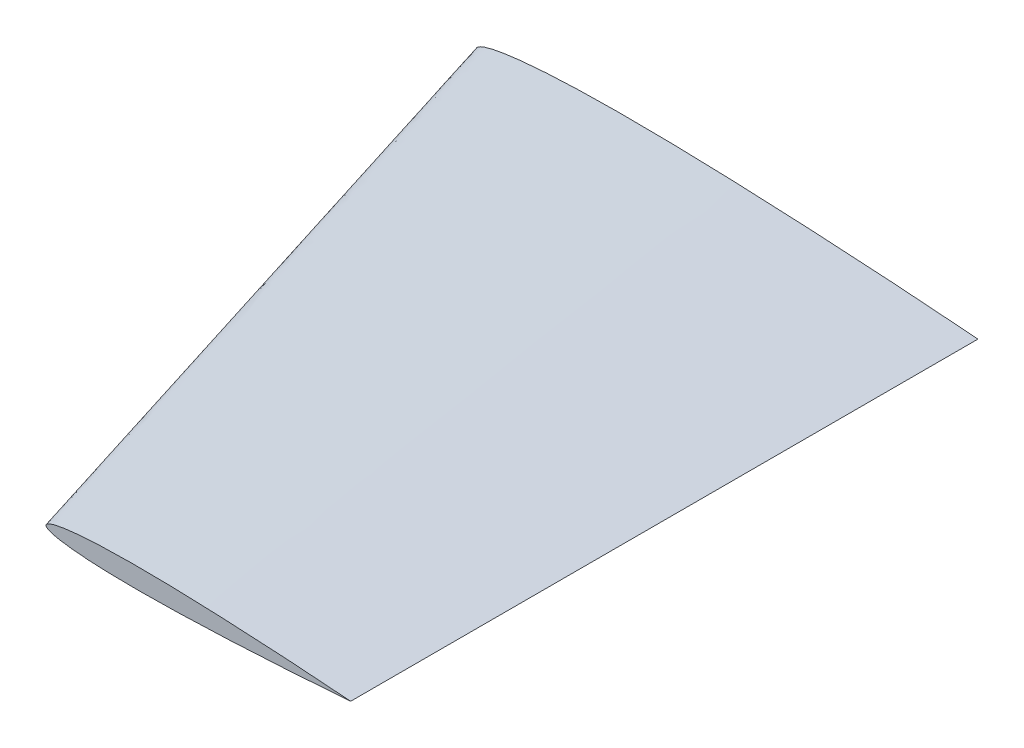
SolidWorks part; units mm, degrees
ref_plane "Спереди" through (0, 0, 0) normal (0, 0, 1) x (1, 0, 0)
ref_plane "Сверху" through (0, 0, 0) normal (0, 1, 0) x (1, 0, 0)
ref_plane "Справа" through (0, 0, 0) normal (1, 0, 0) x (0, 0, -1)
curve "нерв11"
  spline degree 3 poles (280, 0, 0) (279.9079, 0.0075, 0) (279.5399, 0.0373, 0) (278.7133, 0.1038, 0) (277.3394, 0.2136, 0) (275.4234, 0.3662, 0) (272.9728, 0.5586, 0) (269.9976, 0.79, 0) (266.5093, 1.0574, 0) (262.5218, 1.3575, 0) (258.0506, 1.6881, 0) (253.1137, 2.0453, 0) (247.7303, 2.4266, 0) (241.9218, 2.8274, 0) (235.7109, 3.2451, 0) (229.1225, 3.6764, 0) (222.1821, 4.1166, 0) (214.9176, 4.5633, 0) (207.3573, 5.0121, 0) (199.5312, 5.4596, 0) (191.4701, 5.9019, 0) (183.206, 6.336, 0) (174.7713, 6.7567, 0) (166.1995, 7.1603, 0) (157.5242, 7.5437, 0) (148.7797, 7.901, 0) (140.0006, 8.229, 0) (131.2215, 8.5229, 0) (122.4769, 8.7782, 0) (113.8015, 8.9914, 0) (105.2296, 9.1574, 0) (96.7949, 9.273, 0) (88.5305, 9.3348, 0) (80.4692, 9.3396, 0) (72.6428, 9.2852, 0) (65.0822, 9.1701, 0) (57.8173, 8.9931, 0) (50.8764, 8.7536, 0) (44.2874, 8.4522, 0) (38.0758, 8.0908, 0) (32.2665, 7.6702, 0) (26.8819, 7.1938, 0) (21.9435, 6.6644, 0) (17.4704, 6.0858, 0) (13.4799, 5.4625, 0) (9.9879, 4.7977, 0) (7.0046, 4.0976, 0) (4.5467, 3.3651, 0) (2.5986, 2.6073, 0) (1.2079, 1.8188, 0) (0.2201, 0.9919, 0) (0.0666, 0.3003, 0) (0, 0, 0) knots 0 0 0 0 0.000983 0.003927 0.00882 0.015644 0.024371 0.034965 0.047385 0.061583 0.077499 0.095072 0.114231 0.134902 0.157001 0.180442 0.20513 0.23097 0.257857 0.285686 0.314347 0.343727 0.373708 0.404173 0.435002 0.466072 0.497261 0.528445 0.559503 0.590311 0.620748 0.650695 0.680035 0.708653 0.736438 0.76328 0.789079 0.813733 0.837149 0.859235 0.879912 0.899099 0.916729 0.932736 0.947069 0.959681 0.970541 0.979636 0.986978 0.992635 0.996802 1 1 1 1
curve "нерв12"
  spline degree 3 poles (0, 0, 0) (0.0666, -0.3003, 0) (0.2201, -0.9919, 0) (1.2079, -1.8188, 0) (2.5986, -2.6073, 0) (4.5467, -3.3651, 0) (7.0046, -4.0976, 0) (9.9879, -4.7977, 0) (13.4799, -5.4625, 0) (17.4704, -6.0858, 0) (21.9435, -6.6644, 0) (26.8819, -7.1938, 0) (32.2665, -7.6702, 0) (38.0758, -8.0908, 0) (44.2874, -8.4522, 0) (50.8764, -8.7536, 0) (57.8173, -8.9931, 0) (65.0822, -9.1701, 0) (72.6428, -9.2852, 0) (80.4692, -9.3396, 0) (88.5305, -9.3348, 0) (96.7949, -9.273, 0) (105.2296, -9.1574, 0) (113.8015, -8.9914, 0) (122.4769, -8.7782, 0) (131.2215, -8.5229, 0) (140.0006, -8.229, 0) (148.7797, -7.901, 0) (157.5242, -7.5437, 0) (166.1995, -7.1603, 0) (174.7713, -6.7567, 0) (183.206, -6.336, 0) (191.4701, -5.9019, 0) (199.5312, -5.4596, 0) (207.3573, -5.0121, 0) (214.9176, -4.5633, 0) (222.1821, -4.1166, 0) (229.1225, -3.6764, 0) (235.7109, -3.2451, 0) (241.9218, -2.8274, 0) (247.7303, -2.4266, 0) (253.1137, -2.0453, 0) (258.0506, -1.6881, 0) (262.5218, -1.3575, 0) (266.5093, -1.0574, 0) (269.9976, -0.79, 0) (272.9728, -0.5586, 0) (275.4234, -0.3662, 0) (277.3394, -0.2136, 0) (278.7133, -0.1038, 0) (279.5399, -0.0373, 0) (279.9079, -0.0075, 0) (280, 0, 0) knots 0 0 0 0 0.003198 0.007365 0.013022 0.020364 0.029459 0.040319 0.052931 0.067264 0.083271 0.100901 0.120088 0.140765 0.162851 0.186267 0.210921 0.23672 0.263562 0.291347 0.319965 0.349305 0.379252 0.409689 0.440497 0.471555 0.502739 0.533928 0.564998 0.595827 0.626292 0.656273 0.685653 0.714314 0.742143 0.76903 0.79487 0.819558 0.842999 0.865098 0.885769 0.904928 0.922501 0.938417 0.952615 0.965035 0.975629 0.984356 0.99118 0.996073 0.999017 1 1 1 1
curve "Кривая5"
  spline degree 3 poles (55, 0, 0) (55.0536, -0.2413, 0) (55.1769, -0.7971, 0) (55.9706, -1.4615, 0) (57.0882, -2.0952, 0) (58.6536, -2.7041, 0) (60.6287, -3.2927, 0) (63.026, -3.8553, 0) (65.8321, -4.3895, 0) (69.0387, -4.8904, 0) (72.6332, -5.3553, 0) (76.6015, -5.7807, 0) (80.9284, -6.1635, 0) (85.5966, -6.5015, 0) (90.5881, -6.792, 0) (95.8828, -7.0342, 0) (101.4603, -7.2266, 0) (107.2982, -7.3688, 0) (113.3737, -7.4613, 0) (119.6627, -7.505, 0) (126.1406, -7.5012, 0) (132.7816, -7.4515, 0) (139.5595, -7.3586, 0) (146.4477, -7.2252, 0) (153.419, -7.0539, 0) (160.4458, -6.8488, 0) (167.5005, -6.6126, 0) (174.5551, -6.349, 0) (181.582, -6.0619, 0) (188.5532, -5.7538, 0) (195.4413, -5.4295, 0) (202.2191, -5.0914, 0) (208.8599, -4.7426, 0) (215.3376, -4.3872, 0) (221.6264, -4.0276, 0) (227.7016, -3.667, 0) (233.5392, -3.308, 0) (239.1163, -2.9543, 0) (244.4106, -2.6077, 0) (249.4014, -2.272, 0) (254.069, -1.95, 0) (258.3949, -1.6435, 0) (262.3621, -1.3565, 0) (265.955, -1.0909, 0) (269.1593, -0.8497, 0) (271.9624, -0.6348, 0) (274.3532, -0.4489, 0) (276.3224, -0.2943, 0) (277.862, -0.1716, 0) (278.9661, -0.0834, 0) (279.6303, -0.03, 0) (279.926, -0.006, 0) (280, 0, 0) knots 0 0 0 0 0.003198 0.007365 0.013022 0.020364 0.029459 0.040319 0.052931 0.067264 0.083271 0.100901 0.120088 0.140765 0.162851 0.186267 0.210921 0.23672 0.263562 0.291347 0.319965 0.349305 0.379252 0.409689 0.440497 0.471555 0.502739 0.533928 0.564998 0.595827 0.626292 0.656273 0.685653 0.714314 0.742143 0.76903 0.79487 0.819558 0.842999 0.865098 0.885769 0.904928 0.922501 0.938417 0.952615 0.965035 0.975629 0.984356 0.99118 0.996073 0.999017 1 1 1 1
curve "Кривая6"
  spline degree 3 poles (280, 0, 0) (279.926, 0.006, 0) (279.6303, 0.03, 0) (278.9661, 0.0834, 0) (277.862, 0.1716, 0) (276.3224, 0.2943, 0) (274.3532, 0.4489, 0) (271.9624, 0.6348, 0) (269.1593, 0.8497, 0) (265.955, 1.0909, 0) (262.3621, 1.3565, 0) (258.3949, 1.6435, 0) (254.069, 1.95, 0) (249.4014, 2.272, 0) (244.4106, 2.6077, 0) (239.1163, 2.9543, 0) (233.5392, 3.308, 0) (227.7016, 3.667, 0) (221.6264, 4.0276, 0) (215.3376, 4.3872, 0) (208.8599, 4.7426, 0) (202.2191, 5.0914, 0) (195.4413, 5.4295, 0) (188.5532, 5.7538, 0) (181.582, 6.0619, 0) (174.5551, 6.349, 0) (167.5005, 6.6126, 0) (160.4458, 6.8488, 0) (153.419, 7.0539, 0) (146.4477, 7.2252, 0) (139.5595, 7.3586, 0) (132.7816, 7.4515, 0) (126.1406, 7.5012, 0) (119.6627, 7.505, 0) (113.3737, 7.4613, 0) (107.2982, 7.3688, 0) (101.4603, 7.2266, 0) (95.8828, 7.0342, 0) (90.5881, 6.792, 0) (85.5966, 6.5015, 0) (80.9284, 6.1635, 0) (76.6015, 5.7807, 0) (72.6332, 5.3553, 0) (69.0387, 4.8904, 0) (65.8321, 4.3895, 0) (63.026, 3.8553, 0) (60.6287, 3.2927, 0) (58.6536, 2.7041, 0) (57.0882, 2.0952, 0) (55.9706, 1.4615, 0) (55.1769, 0.7971, 0) (55.0536, 0.2413, 0) (55, 0, 0) knots 0 0 0 0 0.000983 0.003927 0.00882 0.015644 0.024371 0.034965 0.047385 0.061583 0.077499 0.095072 0.114231 0.134902 0.157001 0.180442 0.20513 0.23097 0.257857 0.285686 0.314347 0.343727 0.373708 0.404173 0.435002 0.466072 0.497261 0.528445 0.559503 0.590311 0.620748 0.650695 0.680035 0.708653 0.736438 0.76328 0.789079 0.813733 0.837149 0.859235 0.879912 0.899099 0.916729 0.932736 0.947069 0.959681 0.970541 0.979636 0.986978 0.992635 0.996802 1 1 1 1
ref_plane "2 енрв" through (0, 0, 175) normal (0, 0, 1) x (1, 0, 0)
ref_plane "3 нерв" through (0, 0, 350) normal (0, 0, 1) x (1, 0, 0)
sketch "нерв 2" plane through (0, 0, 175) normal (0, 0, 1) x (1, 0, 0)
  spline S0 degree 3 poles (-1705.7299, -947.936) (109.1984, 46.2421) (49.2151, 4.1935) (55.9706, -1.4615) (57.0882, -2.0952) (58.6536, -2.7041) (60.6287, -3.2927) (63.026, -3.8553) (65.8321, -4.3895) (69.0387, -4.8904) (72.6332, -5.3553) (76.6015, -5.7807) (80.9284, -6.1635) (85.5966, -6.5015) (90.5881, -6.792) (95.8828, -7.0342) (101.4603, -7.2266) (107.2982, -7.3688) (113.3737, -7.4613) (119.6627, -7.505) (126.1406, -7.5012) (132.7816, -7.4515) (139.5595, -7.3586) (146.4477, -7.2252) (153.419, -7.0539) (160.4458, -6.8488) (167.5005, -6.6126) (174.5551, -6.349) (181.582, -6.0619) (188.5532, -5.7538) (195.4413, -5.4295) (202.2191, -5.0914) (208.8599, -4.7426) (215.3376, -4.3872) (221.6264, -4.0276) (227.7016, -3.667) (233.5392, -3.308) (239.1163, -2.9543) (244.4106, -2.6077) (249.4014, -2.272) (254.069, -1.95) (258.3949, -1.6435) (262.3621, -1.3565) (265.955, -1.0909) (269.1593, -0.8497) (271.9624, -0.6348) (274.3532, -0.4489) (276.3224, -0.2943) (277.862, -0.1716) (278.9661, -0.0834) (318.8848, 3.1257) (358.1271, 10.1124) (558.6291, -1979.213) knots -0.097805 -0.097805 -0.097805 -0.097805 0.003198 0.007365 0.013022 0.020364 0.029459 0.040319 0.052931 0.067264 0.083271 0.100901 0.120088 0.140765 0.162851 0.186267 0.210921 0.23672 0.263562 0.291347 0.319965 0.349305 0.379252 0.409689 0.440497 0.471555 0.502739 0.533928 0.564998 0.595827 0.626292 0.656273 0.685653 0.714314 0.742143 0.76903 0.79487 0.819558 0.842999 0.865098 0.885769 0.904928 0.922501 0.938417 0.952615 0.965035 0.975629 0.984356 0.99118 0.996073 0.999017 1.521268 1.521268 1.521268 1.521268 only from (55, 0) to (280, 0) construction
  spline S1 degree 3 poles (558.6328, 1979.2493) (358.1276, -10.1125) (318.8851, -3.1257) (278.9661, 0.0834) (277.862, 0.1716) (276.3224, 0.2943) (274.3532, 0.4489) (271.9624, 0.6348) (269.1593, 0.8497) (265.955, 1.0909) (262.3621, 1.3565) (258.3949, 1.6435) (254.069, 1.95) (249.4014, 2.272) (244.4106, 2.6077) (239.1163, 2.9543) (233.5392, 3.308) (227.7016, 3.667) (221.6264, 4.0276) (215.3376, 4.3872) (208.8599, 4.7426) (202.2191, 5.0914) (195.4413, 5.4295) (188.5532, 5.7538) (181.582, 6.0619) (174.5551, 6.349) (167.5005, 6.6126) (160.4458, 6.8488) (153.419, 7.0539) (146.4477, 7.2252) (139.5595, 7.3586) (132.7816, 7.4515) (126.1406, 7.5012) (119.6627, 7.505) (113.3737, 7.4613) (107.2982, 7.3688) (101.4603, 7.2266) (95.8828, 7.0342) (90.5881, 6.792) (85.5966, 6.5015) (80.9284, 6.1635) (76.6015, 5.7807) (72.6332, 5.3553) (69.0387, 4.8904) (65.8321, 4.3895) (63.026, 3.8553) (60.6287, 3.2927) (58.6536, 2.7041) (57.0882, 2.0952) (55.9706, 1.4615) (49.2153, -4.1933) (109.194, -46.239) (-1705.5233, 947.8229) knots -0.521271 -0.521271 -0.521271 -0.521271 0.000983 0.003927 0.00882 0.015644 0.024371 0.034965 0.047385 0.061583 0.077499 0.095072 0.114231 0.134902 0.157001 0.180442 0.20513 0.23097 0.257857 0.285686 0.314347 0.343727 0.373708 0.404173 0.435002 0.466072 0.497261 0.528445 0.559503 0.590311 0.620748 0.650695 0.680035 0.708653 0.736438 0.76328 0.789079 0.813733 0.837149 0.859235 0.879912 0.899099 0.916729 0.932736 0.947069 0.959681 0.970541 0.979636 0.986978 0.992635 0.996802 1.097801 1.097801 1.097801 1.097801 only from (280, 0) to (55, 0) construction
  spline S2 degree 3 poles (55, 0) (55.0536, -0.2413) (55.1769, -0.7971) (55.9706, -1.4615) (57.0882, -2.0952) (58.6536, -2.7041) (60.6287, -3.2927) (63.026, -3.8553) (65.8321, -4.3895) (69.0387, -4.8904) (72.6332, -5.3553) (76.6015, -5.7807) (80.9284, -6.1635) (85.5966, -6.5015) (90.5881, -6.792) (95.8828, -7.0342) (101.4603, -7.2266) (107.2982, -7.3688) (113.3737, -7.4613) (119.6627, -7.505) (126.1406, -7.5012) (132.7816, -7.4515) (139.5595, -7.3586) (146.4477, -7.2252) (153.419, -7.0539) (160.4458, -6.8488) (167.5005, -6.6126) (174.5551, -6.349) (181.582, -6.0619) (188.5532, -5.7538) (195.4413, -5.4295) (202.2191, -5.0914) (208.8599, -4.7426) (215.3376, -4.3872) (221.6264, -4.0276) (227.7016, -3.667) (233.5392, -3.308) (239.1163, -2.9543) (244.4106, -2.6077) (249.4014, -2.272) (254.069, -1.95) (258.3949, -1.6435) (262.3621, -1.3565) (265.955, -1.0909) (269.1593, -0.8497) (271.9624, -0.6348) (274.3532, -0.4489) (276.3224, -0.2943) (277.862, -0.1716) (278.9661, -0.0834) (279.6303, -0.03) (279.926, -0.006) (280, 0) knots 0 0 0 0 0.003198 0.007365 0.013022 0.020364 0.029459 0.040319 0.052931 0.067264 0.083271 0.100901 0.120088 0.140765 0.162851 0.186267 0.210921 0.23672 0.263562 0.291347 0.319965 0.349305 0.379252 0.409689 0.440497 0.471555 0.502739 0.533928 0.564998 0.595827 0.626292 0.656273 0.685653 0.714314 0.742143 0.76903 0.79487 0.819558 0.842999 0.865098 0.885769 0.904928 0.922501 0.938417 0.952615 0.965035 0.975629 0.984356 0.99118 0.996073 0.999017 1 1 1 1
  spline S3 degree 3 poles (280, 0) (279.926, 0.006) (279.6303, 0.03) (278.9661, 0.0834) (277.862, 0.1716) (276.3224, 0.2943) (274.3532, 0.4489) (271.9624, 0.6348) (269.1593, 0.8497) (265.955, 1.0909) (262.3621, 1.3565) (258.3949, 1.6435) (254.069, 1.95) (249.4014, 2.272) (244.4106, 2.6077) (239.1163, 2.9543) (233.5392, 3.308) (227.7016, 3.667) (221.6264, 4.0276) (215.3376, 4.3872) (208.8599, 4.7426) (202.2191, 5.0914) (195.4413, 5.4295) (188.5532, 5.7538) (181.582, 6.0619) (174.5551, 6.349) (167.5005, 6.6126) (160.4458, 6.8488) (153.419, 7.0539) (146.4477, 7.2252) (139.5595, 7.3586) (132.7816, 7.4515) (126.1406, 7.5012) (119.6627, 7.505) (113.3737, 7.4613) (107.2982, 7.3688) (101.4603, 7.2266) (95.8828, 7.0342) (90.5881, 6.792) (85.5966, 6.5015) (80.9284, 6.1635) (76.6015, 5.7807) (72.6332, 5.3553) (69.0387, 4.8904) (65.8321, 4.3895) (63.026, 3.8553) (60.6287, 3.2927) (58.6536, 2.7041) (57.0882, 2.0952) (55.9706, 1.4615) (55.1769, 0.7971) (55.0536, 0.2413) (55, 0) knots 0 0 0 0 0.000983 0.003927 0.00882 0.015644 0.024371 0.034965 0.047385 0.061583 0.077499 0.095072 0.114231 0.134902 0.157001 0.180442 0.20513 0.23097 0.257857 0.285686 0.314347 0.343727 0.373708 0.404173 0.435002 0.466072 0.497261 0.528445 0.559503 0.590311 0.620748 0.650695 0.680035 0.708653 0.736438 0.76328 0.789079 0.813733 0.837149 0.859235 0.879912 0.899099 0.916729 0.932736 0.947069 0.959681 0.970541 0.979636 0.986978 0.992635 0.996802 1 1 1 1
curve "Кривая7"
  spline degree 3 poles (110, 0, 0) (110.0405, -0.1823, 0) (110.1336, -0.6022, 0) (110.7334, -1.1043, 0) (111.5777, -1.583, 0) (112.7605, -2.0431, 0) (114.2528, -2.4878, 0) (116.0641, -2.9129, 0) (118.1842, -3.3165, 0) (120.607, -3.695, 0) (123.3229, -4.0462, 0) (126.3212, -4.3677, 0) (129.5904, -4.6569, 0) (133.1175, -4.9122, 0) (136.8888, -5.1317, 0) (140.8893, -5.3147, 0) (145.1033, -5.4601, 0) (149.5142, -5.5675, 0) (154.1046, -5.6375, 0) (158.8563, -5.6704, 0) (163.7507, -5.6675, 0) (168.7683, -5.63, 0) (173.8894, -5.5598, 0) (179.0938, -5.459, 0) (184.361, -5.3296, 0) (189.6702, -5.1746, 0) (195.0004, -4.9962, 0) (200.3305, -4.797, 0) (205.6397, -4.5801, 0) (210.9069, -4.3473, 0) (216.1112, -4.1023, 0) (221.2322, -3.8468, 0) (226.2497, -3.5833, 0) (231.144, -3.3147, 0) (235.8955, -3.0431, 0) (240.4857, -2.7706, 0) (244.8963, -2.4994, 0) (249.1101, -2.2321, 0) (253.1102, -1.9702, 0) (256.8811, -1.7166, 0) (260.4077, -1.4733, 0) (263.6762, -1.2418, 0) (266.6736, -1.0249, 0) (269.3882, -0.8242, 0) (271.8092, -0.642, 0) (273.9271, -0.4796, 0) (275.7335, -0.3392, 0) (277.2213, -0.2223, 0) (278.3846, -0.1297, 0) (279.2188, -0.063, 0) (279.7206, -0.0227, 0) (279.9441, -0.0045, 0) (280, 0, 0) knots 0 0 0 0 0.003198 0.007365 0.013022 0.020364 0.029459 0.040319 0.052931 0.067264 0.083271 0.100901 0.120088 0.140765 0.162851 0.186267 0.210921 0.23672 0.263562 0.291347 0.319965 0.349305 0.379252 0.409689 0.440497 0.471555 0.502739 0.533928 0.564998 0.595827 0.626292 0.656273 0.685653 0.714314 0.742143 0.76903 0.79487 0.819558 0.842999 0.865098 0.885769 0.904928 0.922501 0.938417 0.952615 0.965035 0.975629 0.984356 0.99118 0.996073 0.999017 1 1 1 1
curve "Кривая8"
  spline degree 3 poles (280, 0, 0) (279.9441, 0.0045, 0) (279.7206, 0.0227, 0) (279.2188, 0.063, 0) (278.3846, 0.1297, 0) (277.2213, 0.2223, 0) (275.7335, 0.3392, 0) (273.9271, 0.4796, 0) (271.8092, 0.642, 0) (269.3882, 0.8242, 0) (266.6736, 1.0249, 0) (263.6762, 1.2418, 0) (260.4077, 1.4733, 0) (256.8811, 1.7166, 0) (253.1102, 1.9702, 0) (249.1101, 2.2321, 0) (244.8963, 2.4994, 0) (240.4857, 2.7706, 0) (235.8955, 3.0431, 0) (231.144, 3.3147, 0) (226.2497, 3.5833, 0) (221.2322, 3.8468, 0) (216.1112, 4.1023, 0) (210.9069, 4.3473, 0) (205.6397, 4.5801, 0) (200.3305, 4.797, 0) (195.0004, 4.9962, 0) (189.6702, 5.1746, 0) (184.361, 5.3296, 0) (179.0938, 5.459, 0) (173.8894, 5.5598, 0) (168.7683, 5.63, 0) (163.7507, 5.6675, 0) (158.8563, 5.6704, 0) (154.1046, 5.6375, 0) (149.5142, 5.5675, 0) (145.1033, 5.4601, 0) (140.8893, 5.3147, 0) (136.8888, 5.1317, 0) (133.1175, 4.9122, 0) (129.5904, 4.6569, 0) (126.3212, 4.3677, 0) (123.3229, 4.0462, 0) (120.607, 3.695, 0) (118.1842, 3.3165, 0) (116.0641, 2.9129, 0) (114.2528, 2.4878, 0) (112.7605, 2.0431, 0) (111.5777, 1.583, 0) (110.7334, 1.1043, 0) (110.1336, 0.6022, 0) (110.0405, 0.1823, 0) (110, 0, 0) knots 0 0 0 0 0.000983 0.003927 0.00882 0.015644 0.024371 0.034965 0.047385 0.061583 0.077499 0.095072 0.114231 0.134902 0.157001 0.180442 0.20513 0.23097 0.257857 0.285686 0.314347 0.343727 0.373708 0.404173 0.435002 0.466072 0.497261 0.528445 0.559503 0.590311 0.620748 0.650695 0.680035 0.708653 0.736438 0.76328 0.789079 0.813733 0.837149 0.859235 0.879912 0.899099 0.916729 0.932736 0.947069 0.959681 0.970541 0.979636 0.986978 0.992635 0.996802 1 1 1 1
sketch "нерв 3" plane through (0, 0, 350) normal (0, 0, 1) x (1, 0, 0)
  spline S0 degree 3 poles (538.6992, 1982.2923) (344.8072, -8.6969) (312.2923, -2.5958) (279.2188, 0.063) (278.3846, 0.1297) (277.2213, 0.2223) (275.7335, 0.3392) (273.9271, 0.4796) (271.8092, 0.642) (269.3882, 0.8242) (266.6736, 1.0249) (263.6762, 1.2418) (260.4077, 1.4733) (256.8811, 1.7166) (253.1102, 1.9702) (249.1101, 2.2321) (244.8963, 2.4994) (240.4857, 2.7706) (235.8955, 3.0431) (231.144, 3.3147) (226.2497, 3.5833) (221.2322, 3.8468) (216.1112, 4.1023) (210.9069, 4.3473) (205.6397, 4.5801) (200.3305, 4.797) (195.0004, 4.9962) (189.6702, 5.1746) (184.361, 5.3296) (179.0938, 5.459) (173.8894, 5.5598) (168.7683, 5.63) (163.7507, 5.6675) (158.8563, 5.6704) (154.1046, 5.6375) (149.5142, 5.5675) (145.1033, 5.4601) (140.8893, 5.3147) (136.8888, 5.1317) (133.1175, 4.9122) (129.5904, 4.6569) (126.3212, 4.3677) (123.3229, 4.0462) (120.607, 3.695) (118.1842, 3.3165) (116.0641, 2.9129) (114.2528, 2.4878) (112.7605, 2.0431) (111.5777, 1.583) (110.7334, 1.1043) (105.1889, -3.537) (159.6036, -40.9432) (-1648.9612, 951.1986) knots -0.572459 -0.572459 -0.572459 -0.572459 0.000983 0.003927 0.00882 0.015644 0.024371 0.034965 0.047385 0.061583 0.077499 0.095072 0.114231 0.134902 0.157001 0.180442 0.20513 0.23097 0.257857 0.285686 0.314347 0.343727 0.373708 0.404173 0.435002 0.466072 0.497261 0.528445 0.559503 0.590311 0.620748 0.650695 0.680035 0.708653 0.736438 0.76328 0.789079 0.813733 0.837149 0.859235 0.879912 0.899099 0.916729 0.932736 0.947069 0.959681 0.970541 0.979636 0.986978 0.992635 0.996802 1.107365 1.107365 1.107365 1.107365 only from (280, 0) to (110, 0) construction
  spline S1 degree 3 poles (-1649.1342, -951.2935) (159.6069, 40.9455) (105.1887, 3.5371) (110.7334, -1.1043) (111.5777, -1.583) (112.7605, -2.0431) (114.2528, -2.4878) (116.0641, -2.9129) (118.1842, -3.3165) (120.607, -3.695) (123.3229, -4.0462) (126.3212, -4.3677) (129.5904, -4.6569) (133.1175, -4.9122) (136.8888, -5.1317) (140.8893, -5.3147) (145.1033, -5.4601) (149.5142, -5.5675) (154.1046, -5.6375) (158.8563, -5.6704) (163.7507, -5.6675) (168.7683, -5.63) (173.8894, -5.5598) (179.0938, -5.459) (184.361, -5.3296) (189.6702, -5.1746) (195.0004, -4.9962) (200.3305, -4.797) (205.6397, -4.5801) (210.9069, -4.3473) (216.1112, -4.1023) (221.2322, -3.8468) (226.2497, -3.5833) (231.144, -3.3147) (235.8955, -3.0431) (240.4857, -2.7706) (244.8963, -2.4994) (249.1101, -2.2321) (253.1102, -1.9702) (256.8811, -1.7166) (260.4077, -1.4733) (263.6762, -1.2418) (266.6736, -1.0249) (269.3882, -0.8242) (271.8092, -0.642) (273.9271, -0.4796) (275.7335, -0.3392) (277.2213, -0.2223) (278.3846, -0.1297) (279.2188, -0.063) (312.292, 2.5957) (344.8065, 8.6967) (538.6931, -1982.2298) knots -0.107368 -0.107368 -0.107368 -0.107368 0.003198 0.007365 0.013022 0.020364 0.029459 0.040319 0.052931 0.067264 0.083271 0.100901 0.120088 0.140765 0.162851 0.186267 0.210921 0.23672 0.263562 0.291347 0.319965 0.349305 0.379252 0.409689 0.440497 0.471555 0.502739 0.533928 0.564998 0.595827 0.626292 0.656273 0.685653 0.714314 0.742143 0.76903 0.79487 0.819558 0.842999 0.865098 0.885769 0.904928 0.922501 0.938417 0.952615 0.965035 0.975629 0.984356 0.99118 0.996073 0.999017 1.572453 1.572453 1.572453 1.572453 only from (110, 0) to (280, 0) construction
  spline S2 degree 3 poles (280, 0) (279.9441, 0.0045) (279.7206, 0.0227) (279.2188, 0.063) (278.3846, 0.1297) (277.2213, 0.2223) (275.7335, 0.3392) (273.9271, 0.4796) (271.8092, 0.642) (269.3882, 0.8242) (266.6736, 1.0249) (263.6762, 1.2418) (260.4077, 1.4733) (256.8811, 1.7166) (253.1102, 1.9702) (249.1101, 2.2321) (244.8963, 2.4994) (240.4857, 2.7706) (235.8955, 3.0431) (231.144, 3.3147) (226.2497, 3.5833) (221.2322, 3.8468) (216.1112, 4.1023) (210.9069, 4.3473) (205.6397, 4.5801) (200.3305, 4.797) (195.0004, 4.9962) (189.6702, 5.1746) (184.361, 5.3296) (179.0938, 5.459) (173.8894, 5.5598) (168.7683, 5.63) (163.7507, 5.6675) (158.8563, 5.6704) (154.1046, 5.6375) (149.5142, 5.5675) (145.1033, 5.4601) (140.8893, 5.3147) (136.8888, 5.1317) (133.1175, 4.9122) (129.5904, 4.6569) (126.3212, 4.3677) (123.3229, 4.0462) (120.607, 3.695) (118.1842, 3.3165) (116.0641, 2.9129) (114.2528, 2.4878) (112.7605, 2.0431) (111.5777, 1.583) (110.7334, 1.1043) (110.1336, 0.6022) (110.0405, 0.1823) (110, 0) knots 0 0 0 0 0.000983 0.003927 0.00882 0.015644 0.024371 0.034965 0.047385 0.061583 0.077499 0.095072 0.114231 0.134902 0.157001 0.180442 0.20513 0.23097 0.257857 0.285686 0.314347 0.343727 0.373708 0.404173 0.435002 0.466072 0.497261 0.528445 0.559503 0.590311 0.620748 0.650695 0.680035 0.708653 0.736438 0.76328 0.789079 0.813733 0.837149 0.859235 0.879912 0.899099 0.916729 0.932736 0.947069 0.959681 0.970541 0.979636 0.986978 0.992635 0.996802 1 1 1 1
  spline S3 degree 3 poles (110, 0) (110.0405, -0.1823) (110.1336, -0.6022) (110.7334, -1.1043) (111.5777, -1.583) (112.7605, -2.0431) (114.2528, -2.4878) (116.0641, -2.9129) (118.1842, -3.3165) (120.607, -3.695) (123.3229, -4.0462) (126.3212, -4.3677) (129.5904, -4.6569) (133.1175, -4.9122) (136.8888, -5.1317) (140.8893, -5.3147) (145.1033, -5.4601) (149.5142, -5.5675) (154.1046, -5.6375) (158.8563, -5.6704) (163.7507, -5.6675) (168.7683, -5.63) (173.8894, -5.5598) (179.0938, -5.459) (184.361, -5.3296) (189.6702, -5.1746) (195.0004, -4.9962) (200.3305, -4.797) (205.6397, -4.5801) (210.9069, -4.3473) (216.1112, -4.1023) (221.2322, -3.8468) (226.2497, -3.5833) (231.144, -3.3147) (235.8955, -3.0431) (240.4857, -2.7706) (244.8963, -2.4994) (249.1101, -2.2321) (253.1102, -1.9702) (256.8811, -1.7166) (260.4077, -1.4733) (263.6762, -1.2418) (266.6736, -1.0249) (269.3882, -0.8242) (271.8092, -0.642) (273.9271, -0.4796) (275.7335, -0.3392) (277.2213, -0.2223) (278.3846, -0.1297) (279.2188, -0.063) (279.7206, -0.0227) (279.9441, -0.0045) (280, 0) knots 0 0 0 0 0.003198 0.007365 0.013022 0.020364 0.029459 0.040319 0.052931 0.067264 0.083271 0.100901 0.120088 0.140765 0.162851 0.186267 0.210921 0.23672 0.263562 0.291347 0.319965 0.349305 0.379252 0.409689 0.440497 0.471555 0.502739 0.533928 0.564998 0.595827 0.626292 0.656273 0.685653 0.714314 0.742143 0.76903 0.79487 0.819558 0.842999 0.865098 0.885769 0.904928 0.922501 0.938417 0.952615 0.965035 0.975629 0.984356 0.99118 0.996073 0.999017 1 1 1 1
sketch "нерв1" plane through (0, 0, 0) normal (0, 0, 1) x (1, 0, 0)
  spline S0 degree 3 poles (-1762.1963, -944.8416) (58.0553, 50.9098) (-6.6783, 4.7827) (1.2079, -1.8188) (2.5986, -2.6073) (4.5467, -3.3651) (7.0046, -4.0976) (9.9879, -4.7977) (13.4799, -5.4625) (17.4704, -6.0858) (21.9435, -6.6644) (26.8819, -7.1938) (32.2665, -7.6702) (38.0758, -8.0908) (44.2874, -8.4522) (50.8764, -8.7536) (57.8173, -8.9931) (65.0822, -9.1701) (72.6428, -9.2852) (80.4692, -9.3396) (88.5305, -9.3348) (96.7949, -9.273) (105.2296, -9.1574) (113.8015, -8.9914) (122.4769, -8.7782) (131.2215, -8.5229) (140.0006, -8.229) (148.7797, -7.901) (157.5242, -7.5437) (166.1995, -7.1603) (174.7713, -6.7567) (183.206, -6.336) (191.4701, -5.9019) (199.5312, -5.4596) (207.3573, -5.0121) (214.9176, -4.5633) (222.1821, -4.1166) (229.1225, -3.6764) (235.7109, -3.2451) (241.9218, -2.8274) (247.7303, -2.4266) (253.1137, -2.0453) (258.0506, -1.6881) (262.5218, -1.3575) (266.5093, -1.0574) (269.9976, -0.79) (272.9728, -0.5586) (275.4234, -0.3662) (277.3394, -0.2136) (278.7133, -0.1038) (324.9436, 3.6127) (370.3838, 11.3899) (576.9467, -1976.1256) knots -0.090941 -0.090941 -0.090941 -0.090941 0.003198 0.007365 0.013022 0.020364 0.029459 0.040319 0.052931 0.067264 0.083271 0.100901 0.120088 0.140765 0.162851 0.186267 0.210921 0.23672 0.263562 0.291347 0.319965 0.349305 0.379252 0.409689 0.440497 0.471555 0.502739 0.533928 0.564998 0.595827 0.626292 0.656273 0.685653 0.714314 0.742143 0.76903 0.79487 0.819558 0.842999 0.865098 0.885769 0.904928 0.922501 0.938417 0.952615 0.965035 0.975629 0.984356 0.99118 0.996073 0.999017 1.484492 1.484492 1.484492 1.484492 only from (0, 0) to (280, 0) construction
  spline S1 degree 3 poles (576.9446, 1976.1049) (370.3835, -11.3898) (324.9434, -3.6127) (278.7133, 0.1038) (277.3394, 0.2136) (275.4234, 0.3662) (272.9728, 0.5586) (269.9976, 0.79) (266.5093, 1.0574) (262.5218, 1.3575) (258.0506, 1.6881) (253.1137, 2.0453) (247.7303, 2.4266) (241.9218, 2.8274) (235.7109, 3.2451) (229.1225, 3.6764) (222.1821, 4.1166) (214.9176, 4.5633) (207.3573, 5.0121) (199.5312, 5.4596) (191.4701, 5.9019) (183.206, 6.336) (174.7713, 6.7567) (166.1995, 7.1603) (157.5242, 7.5437) (148.7797, 7.901) (140.0006, 8.229) (131.2215, 8.5229) (122.4769, 8.7782) (113.8015, 8.9914) (105.2296, 9.1574) (96.7949, 9.273) (88.5305, 9.3348) (80.4692, 9.3396) (72.6428, 9.2852) (65.0822, 9.1701) (57.8173, 8.9931) (50.8764, 8.7536) (44.2874, 8.4522) (38.0758, 8.0908) (32.2665, 7.6702) (26.8819, 7.1938) (21.9435, 6.6644) (17.4704, 6.0858) (13.4799, 5.4625) (9.9879, 4.7977) (7.0046, 4.0976) (4.5467, 3.3651) (2.5986, 2.6073) (1.2079, 1.8188) (-6.6784, -4.7828) (58.0574, -50.9114) (-1762.2894, 944.8925) knots -0.48449 -0.48449 -0.48449 -0.48449 0.000983 0.003927 0.00882 0.015644 0.024371 0.034965 0.047385 0.061583 0.077499 0.095072 0.114231 0.134902 0.157001 0.180442 0.20513 0.23097 0.257857 0.285686 0.314347 0.343727 0.373708 0.404173 0.435002 0.466072 0.497261 0.528445 0.559503 0.590311 0.620748 0.650695 0.680035 0.708653 0.736438 0.76328 0.789079 0.813733 0.837149 0.859235 0.879912 0.899099 0.916729 0.932736 0.947069 0.959681 0.970541 0.979636 0.986978 0.992635 0.996802 1.090943 1.090943 1.090943 1.090943 only from (280, 0) to (0, 0) construction
  spline S2 degree 3 poles (0, 0) (0.0666, -0.3003) (0.2201, -0.9919) (1.2079, -1.8188) (2.5986, -2.6073) (4.5467, -3.3651) (7.0046, -4.0976) (9.9879, -4.7977) (13.4799, -5.4625) (17.4704, -6.0858) (21.9435, -6.6644) (26.8819, -7.1938) (32.2665, -7.6702) (38.0758, -8.0908) (44.2874, -8.4522) (50.8764, -8.7536) (57.8173, -8.9931) (65.0822, -9.1701) (72.6428, -9.2852) (80.4692, -9.3396) (88.5305, -9.3348) (96.7949, -9.273) (105.2296, -9.1574) (113.8015, -8.9914) (122.4769, -8.7782) (131.2215, -8.5229) (140.0006, -8.229) (148.7797, -7.901) (157.5242, -7.5437) (166.1995, -7.1603) (174.7713, -6.7567) (183.206, -6.336) (191.4701, -5.9019) (199.5312, -5.4596) (207.3573, -5.0121) (214.9176, -4.5633) (222.1821, -4.1166) (229.1225, -3.6764) (235.7109, -3.2451) (241.9218, -2.8274) (247.7303, -2.4266) (253.1137, -2.0453) (258.0506, -1.6881) (262.5218, -1.3575) (266.5093, -1.0574) (269.9976, -0.79) (272.9728, -0.5586) (275.4234, -0.3662) (277.3394, -0.2136) (278.7133, -0.1038) (279.5399, -0.0373) (279.9079, -0.0075) (280, 0) knots 0 0 0 0 0.003198 0.007365 0.013022 0.020364 0.029459 0.040319 0.052931 0.067264 0.083271 0.100901 0.120088 0.140765 0.162851 0.186267 0.210921 0.23672 0.263562 0.291347 0.319965 0.349305 0.379252 0.409689 0.440497 0.471555 0.502739 0.533928 0.564998 0.595827 0.626292 0.656273 0.685653 0.714314 0.742143 0.76903 0.79487 0.819558 0.842999 0.865098 0.885769 0.904928 0.922501 0.938417 0.952615 0.965035 0.975629 0.984356 0.99118 0.996073 0.999017 1 1 1 1
  spline S3 degree 3 poles (280, 0) (279.9079, 0.0075) (279.5399, 0.0373) (278.7133, 0.1038) (277.3394, 0.2136) (275.4234, 0.3662) (272.9728, 0.5586) (269.9976, 0.79) (266.5093, 1.0574) (262.5218, 1.3575) (258.0506, 1.6881) (253.1137, 2.0453) (247.7303, 2.4266) (241.9218, 2.8274) (235.7109, 3.2451) (229.1225, 3.6764) (222.1821, 4.1166) (214.9176, 4.5633) (207.3573, 5.0121) (199.5312, 5.4596) (191.4701, 5.9019) (183.206, 6.336) (174.7713, 6.7567) (166.1995, 7.1603) (157.5242, 7.5437) (148.7797, 7.901) (140.0006, 8.229) (131.2215, 8.5229) (122.4769, 8.7782) (113.8015, 8.9914) (105.2296, 9.1574) (96.7949, 9.273) (88.5305, 9.3348) (80.4692, 9.3396) (72.6428, 9.2852) (65.0822, 9.1701) (57.8173, 8.9931) (50.8764, 8.7536) (44.2874, 8.4522) (38.0758, 8.0908) (32.2665, 7.6702) (26.8819, 7.1938) (21.9435, 6.6644) (17.4704, 6.0858) (13.4799, 5.4625) (9.9879, 4.7977) (7.0046, 4.0976) (4.5467, 3.3651) (2.5986, 2.6073) (1.2079, 1.8188) (0.2201, 0.9919) (0.0666, 0.3003) (0, 0) knots 0 0 0 0 0.000983 0.003927 0.00882 0.015644 0.024371 0.034965 0.047385 0.061583 0.077499 0.095072 0.114231 0.134902 0.157001 0.180442 0.20513 0.23097 0.257857 0.285686 0.314347 0.343727 0.373708 0.404173 0.435002 0.466072 0.497261 0.528445 0.559503 0.590311 0.620748 0.650695 0.680035 0.708653 0.736438 0.76328 0.789079 0.813733 0.837149 0.859235 0.879912 0.899099 0.916729 0.932736 0.947069 0.959681 0.970541 0.979636 0.986978 0.992635 0.996802 1 1 1 1
loft "По сечениям1" add profiles "нерв1", "нерв 2", "нерв 3"
